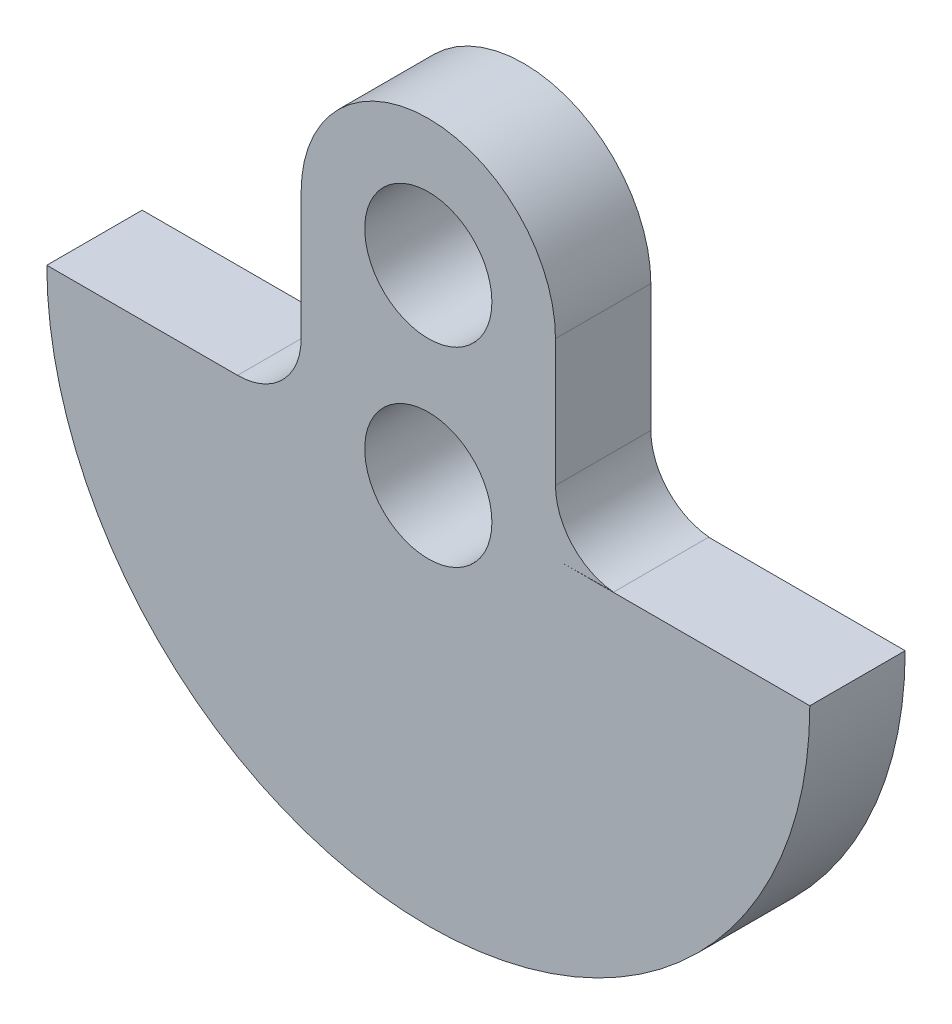
SolidWorks part; units mm, degrees
ref_plane "Front Plane" through (0, 0, 0) normal (0, 0, 1) x (1, 0, 0)
ref_plane "Top Plane" through (0, 0, 0) normal (0, 1, 0) x (1, 0, 0)
ref_plane "Right Plane" through (0, 0, 0) normal (1, 0, 0) x (0, 0, -1)
sketch "Sketch2" plane through (0, 0, 0) normal (0, 0, 1) x (1, 0, 0)
  line L0 (-60, 0) -> (60, 0)
  arc A0 (-60, 0) -> (60, 0) centre (0, 0) ccw
  dimension "D1" = 120
extrude "Boss-Extrude1" add sketch "Sketch2" along normal blind 15
sketch "Sketch3" plane through (0, 0, 15) normal (0, 0, 1) x (1, 0, 0)
  line L1 (60, 0) -> (-60, 0) construction
  line L3 (-20, 30) -> (-20, 0)
  line L4 (-20, 0) -> (20, 0)
  line L5 (20, 30) -> (20, 0)
  arc A0 (20, 30) -> (-20, 30) centre (0, 30) ccw
  dimension "D2" = 40
extrude "Boss-Extrude2" add sketch "Sketch3" against normal blind 15
sketch "Sketch4" plane through (0, 0, 15) normal (0, 0, 1) x (1, 0, 0)
  line L0 (20, 10) -> (20, 0)
  line L1 (20, 0) -> (29.1231, 0.0385)
  arc A0 (20, 10) -> (29.1231, 0.0385) centre (30, 10) ccw
extrude "Boss-Extrude4" add sketch "Sketch4" against normal blind 15
sketch "Sketch6" plane through (0, 0, 15) normal (0, 0, 1) x (1, 0, 0)
  line L2 (-20, 10) -> (-20, 0)
  line L3 (-20, 0) -> (-60, 0) construction
  line L4 (-20, 30) -> (-20, 0) construction
  line L5 (-20, 0) -> (-30, 0)
  arc A0 (-30, 0) -> (-20, 10) centre (-30, 10) ccw
extrude "Boss-Extrude5" add sketch "Sketch6" against normal blind 15
sketch "Sketch7" plane through (0, 0, 15) normal (0, 0, 1) x (1, 0, 0)
  circle A0 centre (0, 30) radius 10
  dimension "D2" = 20
extrude "Cut-Extrude1" cut sketch "Sketch7" against normal blind 15
sketch "Sketch8" plane through (0, 0, 15) normal (0, 0, 1) x (1, 0, 0)
  circle A0 centre (0, 0) radius 10
  dimension "D1" = 20
extrude "Cut-Extrude2" cut sketch "Sketch8" against normal blind 15
